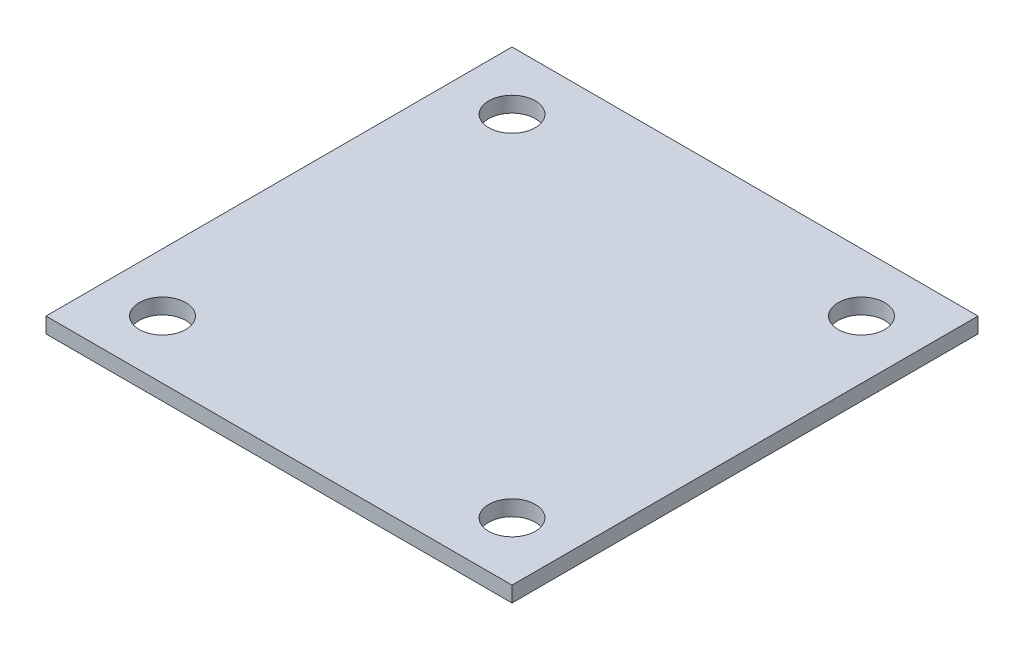
SolidWorks part; units mm, degrees
ref_plane "前视基准面" through (0, 0, 0) normal (0, 0, 1) x (1, 0, 0)
ref_plane "上视基准面" through (0, 0, 0) normal (0, 1, 0) x (1, 0, 0)
ref_plane "右视基准面" through (0, 0, 0) normal (1, 0, 0) x (0, 0, -1)
sketch "草图4" plane through (0, 0, 0) normal (0, 1, 0) x (1, 0, 0)
  line L1 (-30, 30) -> (30, 30)
  line L2 (-30, 30) -> (-30, -30)
  line L3 (-30, -30) -> (30, -30)
  line L4 (30, 30) -> (30, -30)
  line L5 (-30, 30) -> (30, -30) construction
  line L6 (-30, -30) -> (30, 30) construction
  point P0 (0, 0)
extrude "凸台-拉伸2" add sketch "草图4" along normal blind 2
sketch "草图5" plane through (0, 2, 0) normal (0, 1, 0) x (1, 0, 0)
  circle A0 centre (-22.5, 22.5) radius 3
  circle A2 centre (22.5, 22.5) radius 3
  circle A3 centre (-22.5, -22.5) radius 3
  circle A4 centre (22.5, -22.5) radius 3
  dimension "D1" = 2
  dimension "D2" = 2
  dimension "D3" = 2
extrude "切除-拉伸1" cut sketch "草图5" against normal through all
